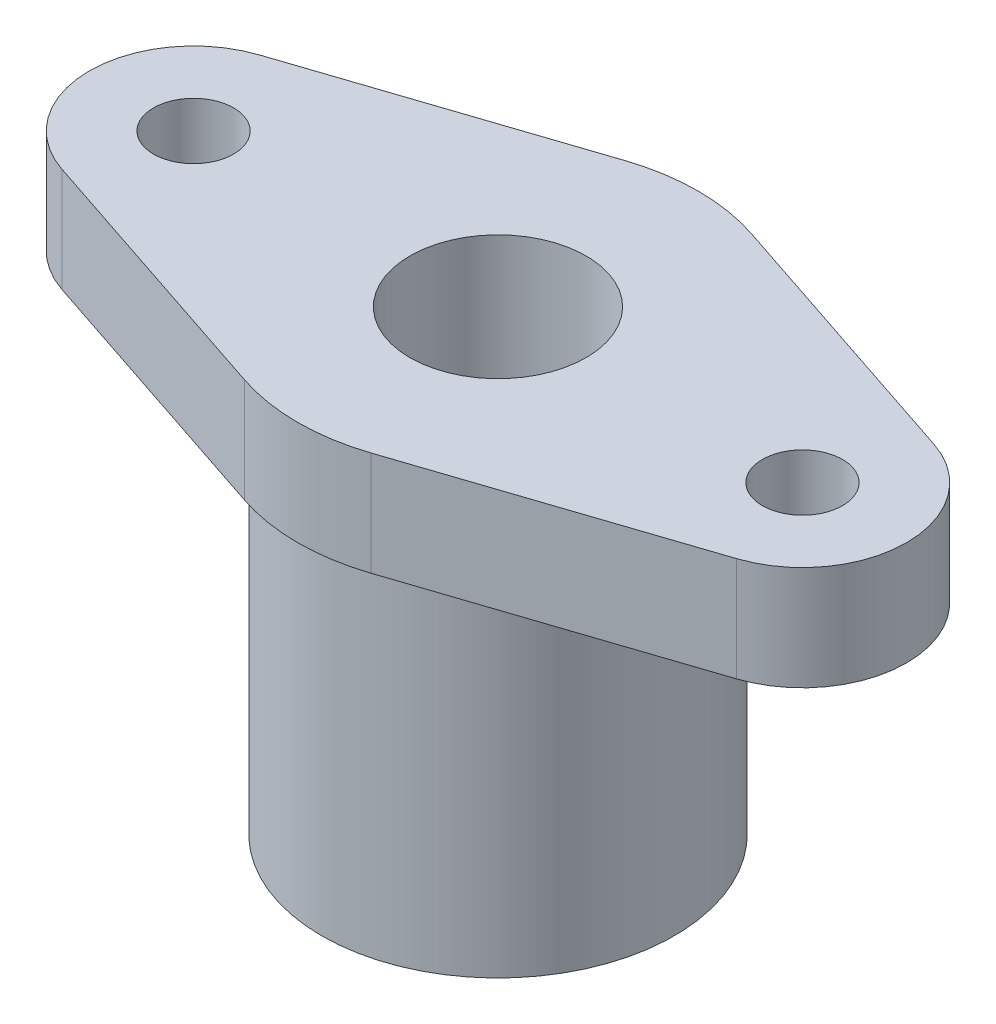
SolidWorks part; units mm, degrees
ref_plane "Front Plane" through (0, 0, 0) normal (0, 0, 1) x (1, 0, 0)
ref_plane "Top Plane" through (0, 0, 0) normal (0, 1, 0) x (1, 0, 0)
ref_plane "Right Plane" through (0, 0, 0) normal (1, 0, 0) x (0, 0, -1)
sketch "Sketch1" plane through (0, 0, 0) normal (0, 1, 0) x (1, 0, 0)
  line L0 (0, 25) -> (0, 0) construction
  line L1 (38, 0) -> (-38, 0) construction
  line L2 (-42.1053, 12.3348) -> (-7.8947, 23.7207)
  line L3 (-42.1053, -12.3348) -> (-7.8947, -23.7207)
  line L4 (42.1053, -12.3348) -> (7.8947, -23.7207)
  line L5 (42.1053, 12.3348) -> (7.8947, 23.7207)
  arc A0 (-7.8947, -23.7207) -> (7.8947, -23.7207) centre (0, 0) ccw
  arc A1 (-42.1053, 12.3348) -> (-42.1053, -12.3348) centre (-38, 0) ccw
  arc A2 (42.1053, 12.3348) -> (42.1053, -12.3348) centre (38, 0) cw
  arc A3 (7.8947, 23.7207) -> (-7.8947, 23.7207) centre (0, 0) ccw
  circle A4 centre (38, 0) radius 5
  circle A5 centre (-38, 0) radius 5
  dimension "D2" = 26
  dimension "D3" = 50
  dimension "D4" = 10
  dimension "D1" = 76
extrude "Boss-Extrude1" add sketch "Sketch1" against normal blind 13
sketch "Sketch2" plane through (0, -13, 0) normal (0, -1, 0) x (1, 0, 0)
  circle A0 centre (0, 0) radius 22
extrude "Boss-Extrude2" add sketch "Sketch2" along normal blind 44
sketch "Sketch3" plane through (0, 0, 0) normal (0, 0, 1) x (1, 0, 0)
  line L0 (0, 0) -> (0, -57) construction
  line L1 (-22, -57) -> (22, -57) construction
  line L2 (0, 0) -> (-11, 0)
  line L3 (-42.1053, 0) -> (-7.8947, 0) construction
  line L4 (-11, 0) -> (-11, -50.6491)
  line L5 (-11, -50.6491) -> (-22, -57)
  line L6 (-22, -57) -> (0, -57)
  line L7 (0, 0) -> (0, -57)
  dimension "D1" = 30
  dimension "D2" = 22
revolve "Cut-Revolve2" cut sketch "Sketch3" angle 360 about L0
